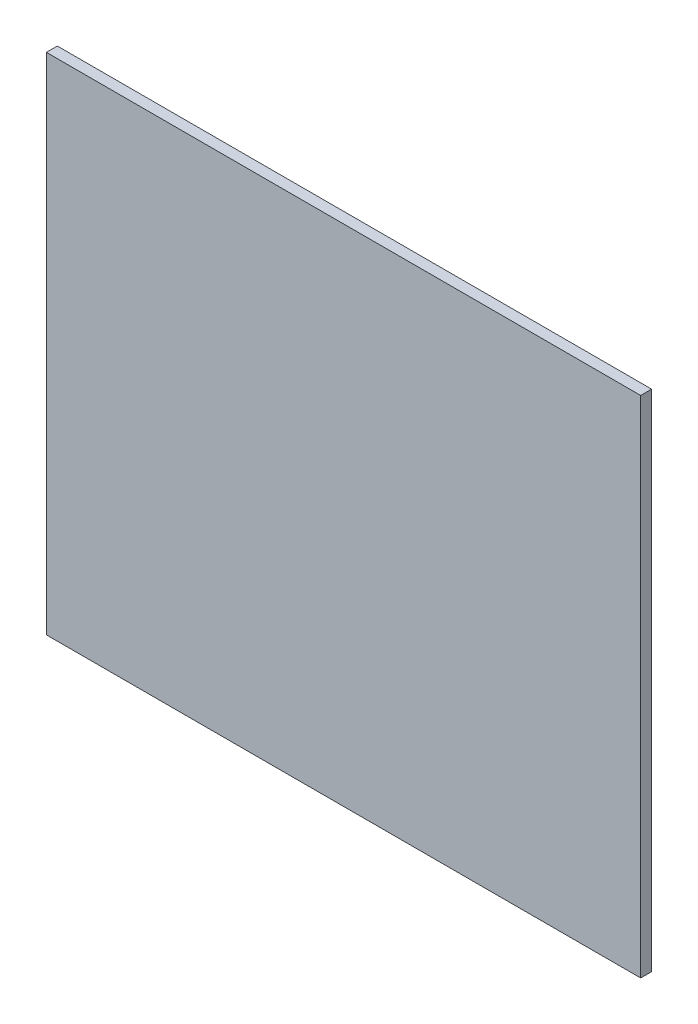
SolidWorks part; units mm, degrees
material "BUTYL"
ref_plane "Front Plane" through (0, 0, 0) normal (0, 0, 1) x (1, 0, 0)
ref_plane "Top Plane" through (0, 0, 0) normal (0, 1, 0) x (1, 0, 0)
ref_plane "Right Plane" through (0, 0, 0) normal (1, 0, 0) x (0, 0, -1)
sketch "Sketch1" plane through (0, 0, 0) normal (0, 0, 1) x (1, 0, 0)
  line L1 (0, 0) -> (55.1656, 0)
  line L2 (0, 0) -> (0, 46.8279)
  line L3 (0, 46.8279) -> (55.1656, 46.8279)
  line L4 (55.1656, 0) -> (55.1656, 46.8279)
  dimension "D1" = 55.1656
  dimension "D2" = 46.8279
extrude "Boss-Extrude1" add sketch "Sketch1" along normal blind 1.016 contours L2 L3 L4 L1
equation "\"compstripwidth\" = 2 + 0.171875in"
equation "\"compstriplength\"= 1.697720242 + 0.145897833in"
equation "\"compdepth\"= 0.04in"
equation "\"D1@Sketch1\"=\"compstripwidth\""
equation "\"D2@Sketch1\"=\"compstriplength\""
equation "\"D1@Boss-Extrude1\"=\"compdepth\""
